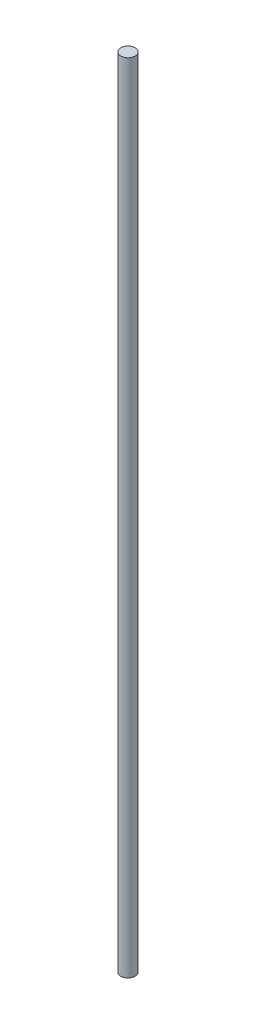
SolidWorks part; units mm, degrees
material "Plain Carbon Steel"
ref_plane "Front" through (0, 0, 0) normal (0, 0, 1) x (1, 0, 0)
ref_plane "Top" through (0, 0, 0) normal (0, 1, 0) x (1, 0, 0)
ref_plane "Right" through (0, 0, 0) normal (1, 0, 0) x (0, 0, -1)
sketch "Sketch1" plane through (0, 0, 0) normal (0, 1, 0) x (1, 0, 0)
  circle A0 centre (0, 0) radius 4
  dimension "D1" = 8
extrude "Boss-Extrude1" add sketch "Sketch1" along normal mid plane 442
